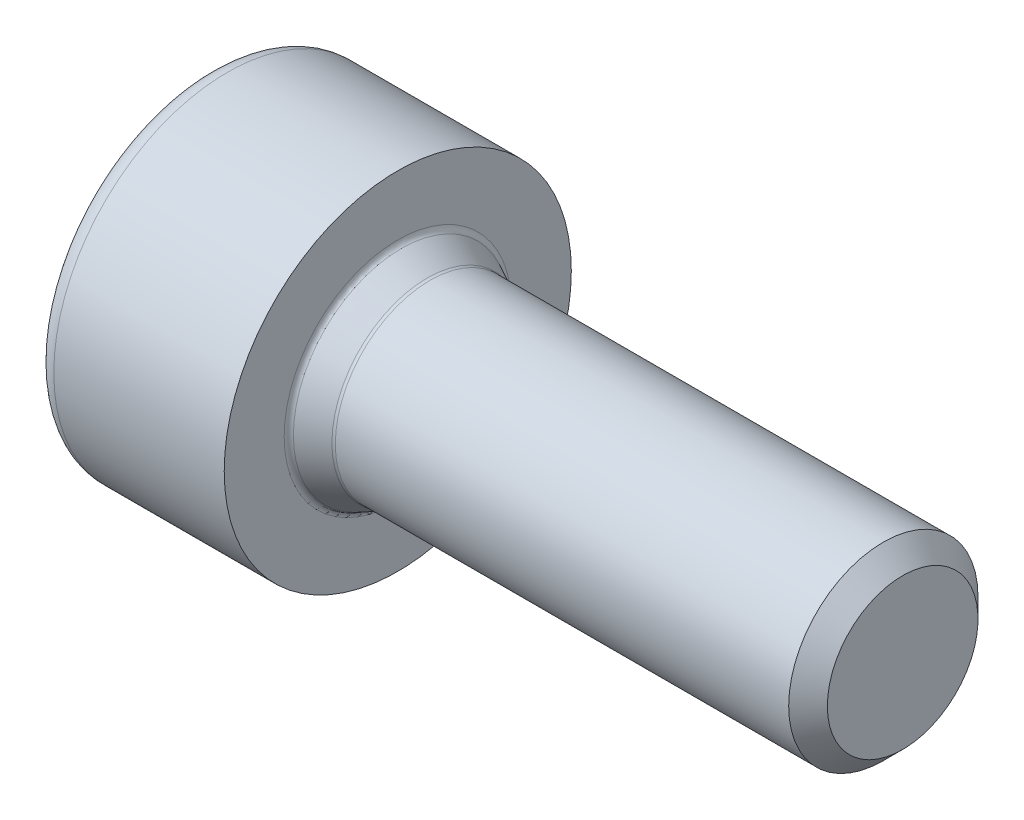
SolidWorks part; units mm, degrees
ref_plane "Front Plane" through (0, 0, 0) normal (0, 0, 1) x (1, 0, 0)
ref_plane "Top Plane" through (0, 0, 0) normal (0, 1, 0) x (1, 0, 0)
ref_plane "Right Plane" through (0, 0, 0) normal (1, 0, 0) x (0, 0, -1)
ref_plane "Plane1" through (0, 0, 0) normal (0, 0, 1) x (1, 0, 0)
sketch "Sketch1" plane through (0, 0, 0) normal (0, 0, 1) x (1, 0, 0)
  line L0 (-0.4283, 0) -> (-1.15, 1.25)
  line L1 (-1.15, 1.25) -> (-3, 1.25)
  line L2 (-3, 1.25) -> (-3, 2.45)
  line L3 (-2.7, 2.75) -> (0, 2.75)
  line L4 (0, 2.75) -> (0, 1.8)
  line L5 (0.0562, 1.7101) -> (0.4662, 1.5101)
  line L6 (0.51, 1.5) -> (7.6935, 1.5)
  line L7 (7.6935, 1.5) -> (8, 1.1935)
  line L8 (8, 1.1935) -> (8, 0)
  line L9 (8, 0) -> (-0.4283, 0)
  line L10 (8, 0) -> (-0.4283, 0) construction
  arc A0 (-3, 2.45) -> (-2.7, 2.75) centre (-2.7, 2.45) cw
  arc A1 (0, 1.8) -> (0.0562, 1.7101) centre (0.1, 1.8) ccw
  arc A2 (0.4662, 1.5101) -> (0.51, 1.5) centre (0.51, 1.6) ccw
revolve "Revolve1" add sketch "Sketch1" angle 360 about L10
cosmetic thread "Cosmetic Thread1" parameters "D1"=1.5, "D2"=2.387
ref_plane "Plane2" through (-1.15, 0, 0) normal (1, 0, 0) x (0, 0, -1)
sketch "Sketch2" plane through (-1.15, 0, 0) normal (1, 0, 0) x (0, 0, -1)
  line L0 (-1.25, 0.7217) -> (-1.25, -0.7217)
  line L1 (-1.25, -0.7217) -> (0, -1.4434)
  line L2 (0, -1.4434) -> (1.25, -0.7217)
  line L3 (1.25, -0.7217) -> (1.25, 0.7217)
  line L4 (1.25, 0.7217) -> (0, 1.4434)
  line L5 (0, 1.4434) -> (-1.25, 0.7217)
extrude "Cut-Extrude1" cut sketch "Sketch2" against normal blind 2.6
